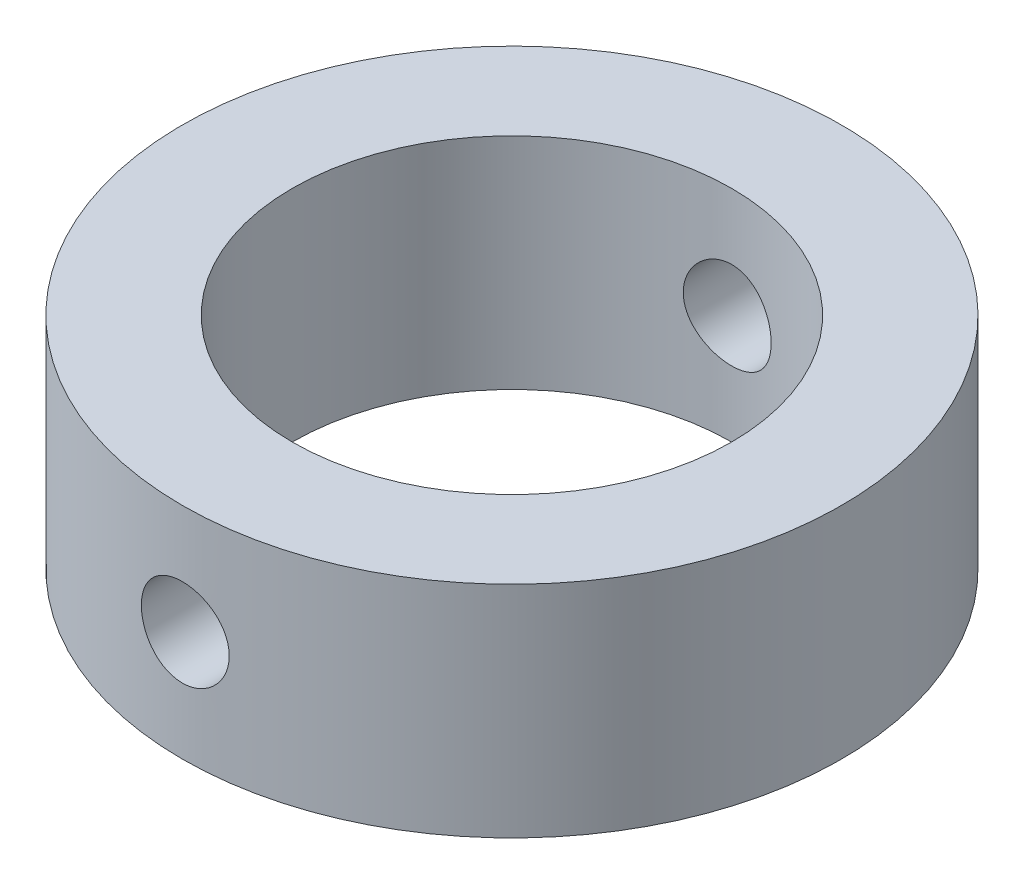
SolidWorks part; units mm, degrees
ref_plane "Front Plane" through (0, 0, 0) normal (0, 0, 1) x (1, 0, 0)
ref_plane "Top Plane" through (0, 0, 0) normal (0, 1, 0) x (1, 0, 0)
ref_plane "Right Plane" through (0, 0, 0) normal (1, 0, 0) x (0, 0, -1)
sketch "Sketch1" plane through (0, 0, 0) normal (0, 1, 0) x (1, 0, 0)
  circle A0 centre (0, 0) radius 22.5
  circle A1 centre (0, 0) radius 15
  dimension "D1" = 45
  dimension "D2" = 30
extrude "Boss-Extrude1" add sketch "Sketch1" along normal blind 15
sketch "Sketch2" plane through (0, 0, 0) normal (0, 0, 1) x (1, 0, 0)
  circle A0 centre (0, 7.5) radius 3
  point P4 (0, 0)
  point P6 (-37.1342, 16.7168)
  dimension "D2" = 6
  dimension "D1" = 7.5
extrude "Cut-Extrude1" cut sketch "Sketch2" against normal through all both and the other way through all
